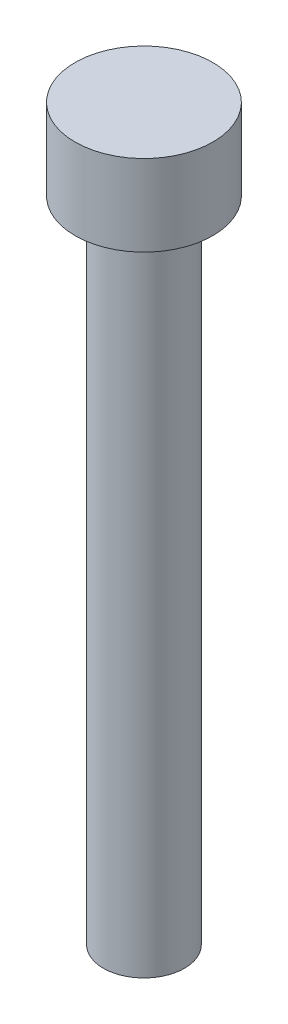
SolidWorks part; units mm, degrees
ref_plane "Front Plane" through (0, 0, 0) normal (0, 0, 1) x (1, 0, 0)
ref_plane "Top Plane" through (0, 0, 0) normal (0, 1, 0) x (1, 0, 0)
ref_plane "Right Plane" through (0, 0, 0) normal (1, 0, 0) x (0, 0, -1)
sketch "Sketch1" plane through (0, 0, 0) normal (0, 1, 0) x (1, 0, 0)
  circle A0 centre (0, 0) radius 2.5
  dimension "D1" = 5
extrude "Boss-Extrude1" add sketch "Sketch1" along normal blind 40
sketch "Sketch2" plane through (0, 40, 0) normal (0, 1, 0) x (1, 0, 0)
  circle A0 centre (0, 0) radius 4.25
  dimension "D1" = 8.5
extrude "Boss-Extrude2" add sketch "Sketch2" along normal blind 5 contours A0
